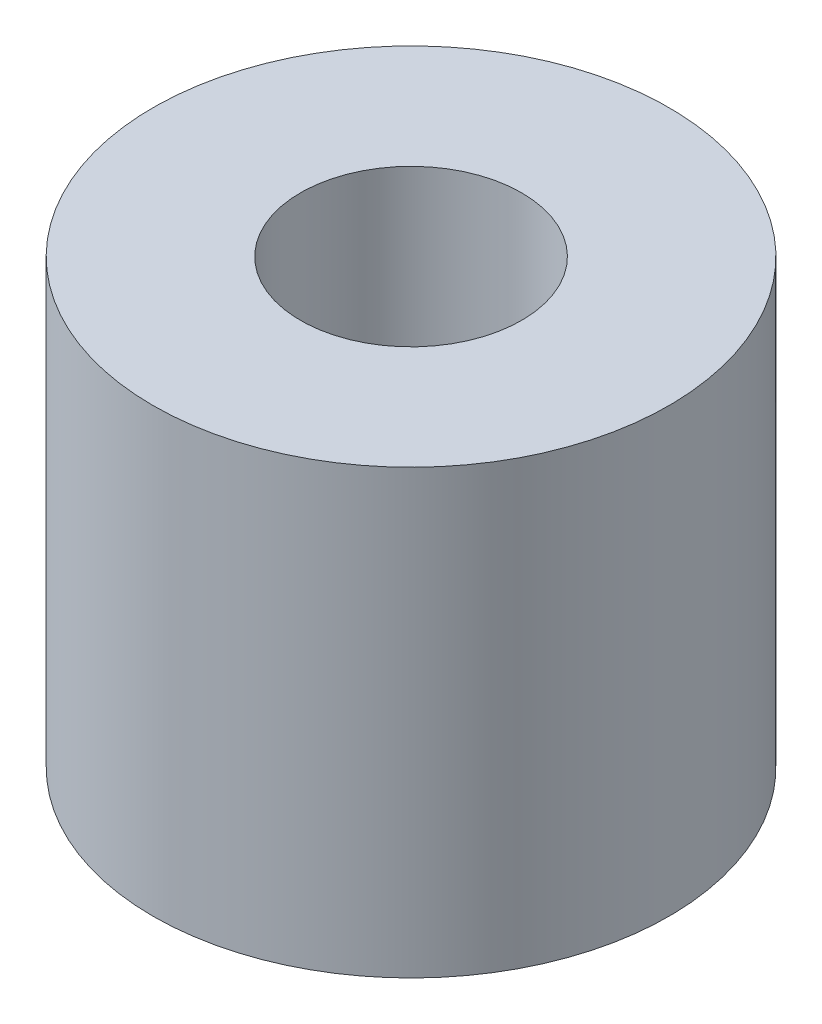
SolidWorks part; units mm, degrees
ref_plane "Front Plane" through (0, 0, 0) normal (0, 0, 1) x (1, 0, 0)
ref_plane "Top Plane" through (0, 0, 0) normal (0, 1, 0) x (1, 0, 0)
ref_plane "Right Plane" through (0, 0, 0) normal (1, 0, 0) x (0, 0, -1)
sketch "Esquisse1" plane through (0, 0, 0) normal (0, 1, 0) x (1, 0, 0)
  circle A0 centre (0, 0) radius 17.5
  dimension "D1" = 35
extrude "Boss.-Extru.1" add sketch "Esquisse1" along normal blind 30
sketch "Esquisse2" plane through (0, 0, 0) normal (0, -1, 0) x (1, 0, 0)
  circle A2 centre (0, 0) radius 7.5
  circle A3 centre (0, 0) radius 7.5
  dimension "D1" = 10
extrude "Enlèv. mat.-Extru.1" cut sketch "Esquisse2" against normal blind 30
